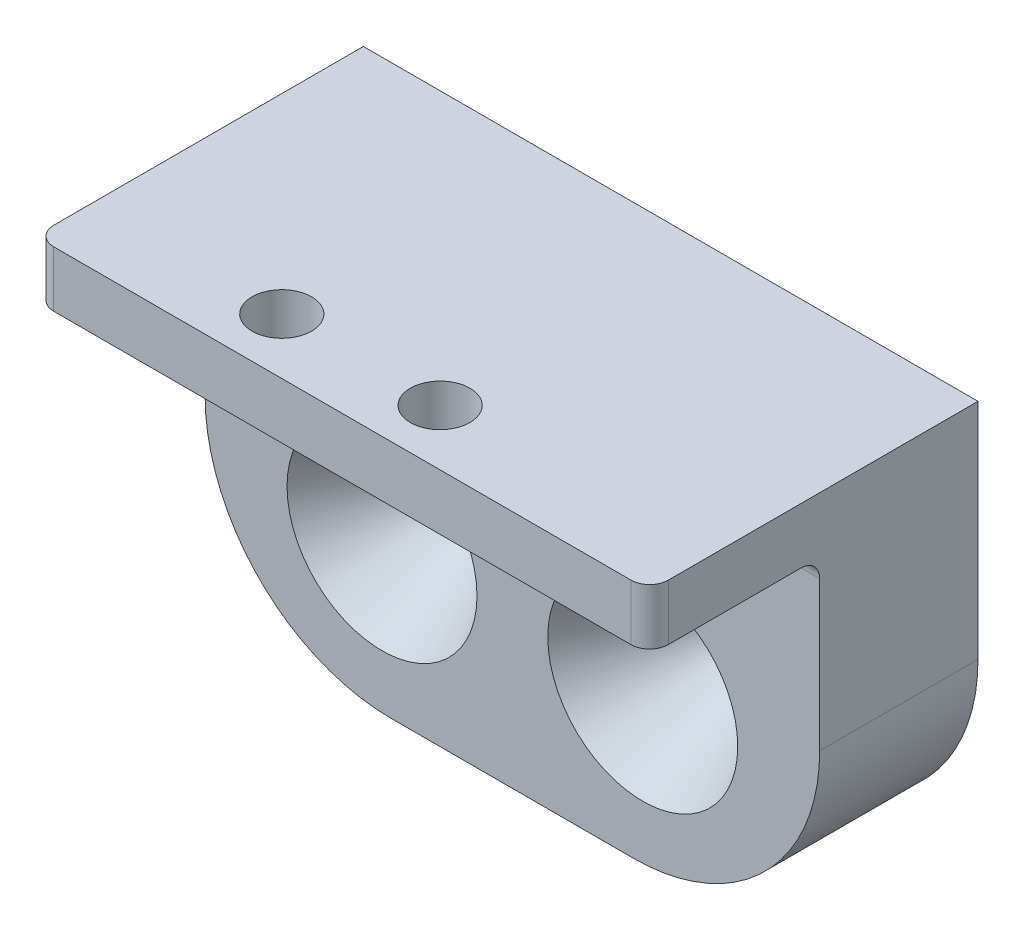
SolidWorks part; units mm, degrees
ref_plane "前视基准面" through (0, 0, 0) normal (0, 0, 1) x (1, 0, 0)
ref_plane "上视基准面" through (0, 0, 0) normal (0, 1, 0) x (1, 0, 0)
ref_plane "右视基准面" through (0, 0, 0) normal (1, 0, 0) x (0, 0, -1)
other "Configuration Table"
sketch "草图1" plane through (0, 0, 0) normal (0, 0, 1) x (1, 0, 0)
  line L1 (-16.5, -8) -> (16.5, -8)
  line L2 (-16.5, -8) -> (-16.5, 8)
  line L3 (-16.5, 8) -> (16.5, 8)
  line L4 (16.5, -8) -> (16.5, 8)
  line L5 (-16.5, -8) -> (16.5, 8) construction
  line L6 (-16.5, 8) -> (16.5, -8) construction
  point P0 (0, 0)
extrude "凸台-拉伸1" add sketch "草图1" against normal blind 8.5
sketch "草图3" plane through (0, 0, 0) normal (0, 1, 0) x (1, 0, 0)
  line L0 (0, 0) -> (-7, 0) construction
  line L6 (-7, 0) -> (-7, 6.1)
  line L7 (-7, 0) -> (-12.1, 0)
  line L8 (-12.1, 0) -> (-8.5782, 6.1)
  line L9 (-8.5782, 6.1) -> (-7, 6.1)
  dimension "D1" = 60
revolve "切除-旋转1" cut sketch "草图3" angle 360 about L6
mirror "镜向1" about plane through (0, 0, 0) normal (1, 0, 0) of "切除-旋转1"
sketch "草图4" plane through (0, 8, 0) normal (0, 1, 0) x (1, 0, 0)
  line L0 (-16.5, 0) -> (-10.5, 0)
  line L1 (16.5, 0) -> (-16.5, 0) construction
  line L2 (16.5, 0) -> (6.5, 0)
  line L3 (-10.5, 0) -> (6.5, 0)
  line L4 (-16.5, 0) -> (-16.5, -9.13)
  line L5 (-16.5, -9.13) -> (16.5, -9.13)
  line L6 (16.5, -9.13) -> (16.5, 0)
  line L7 (-10.5, 0) -> (-10.5, -9.13) construction
  line L8 (6.5, 0) -> (6.5, -9.13) construction
  line L9 (-2, 0) -> (-2, -9.13) construction
  line L10 (-10.5, -3.13) -> (6.5, -3.13) construction
  line L11 (-2, -3.13) -> (-10.5, -9.13) construction
  line L12 (-2, -3.13) -> (6.5, -9.13) construction
  circle A2 centre (-6.25, -6.13) radius 1.6
  circle A3 centre (2.25, -6.13) radius 1.6
  dimension "D1" = 6
extrude "凸台-拉伸2" add sketch "草图4" along normal blind 6
fillet "圆角1" radius 10 2 edges at (16.5, -8, -4.25) (-16.5, -8, -4.25)
sketch "草图5" plane through (16.5, 0, 0) normal (1, 0, 0) x (0, 0, -1)
  line L1 (0, 14) -> (8.5, 14)
  line L2 (0, 14) -> (0, 8)
  line L3 (0, 8) -> (8.5, 8)
  line L4 (8.5, 14) -> (8.5, 8)
extrude "凸台-拉伸3" add sketch "草图5" against normal up to surface (33 mm away) up to face at (-16.5, 11, 4.565)
sketch "草图6" plane through (16.5, 0, 0) normal (1, 0, 0) x (0, 0, -1)
  line L1 (-9.13, 8) -> (0, 8)
  line L2 (-9.13, 8) -> (-9.13, 11)
  line L3 (-9.13, 11) -> (0, 11)
  line L4 (0, 8) -> (0, 11)
extrude "切除-拉伸1" cut sketch "草图6" against normal up to next
fillet "圆角2" radius 1 3 edges at (-16.5, 12.5, 9.13) (16.5, 12.5, 9.13) (0, 11, 0)
